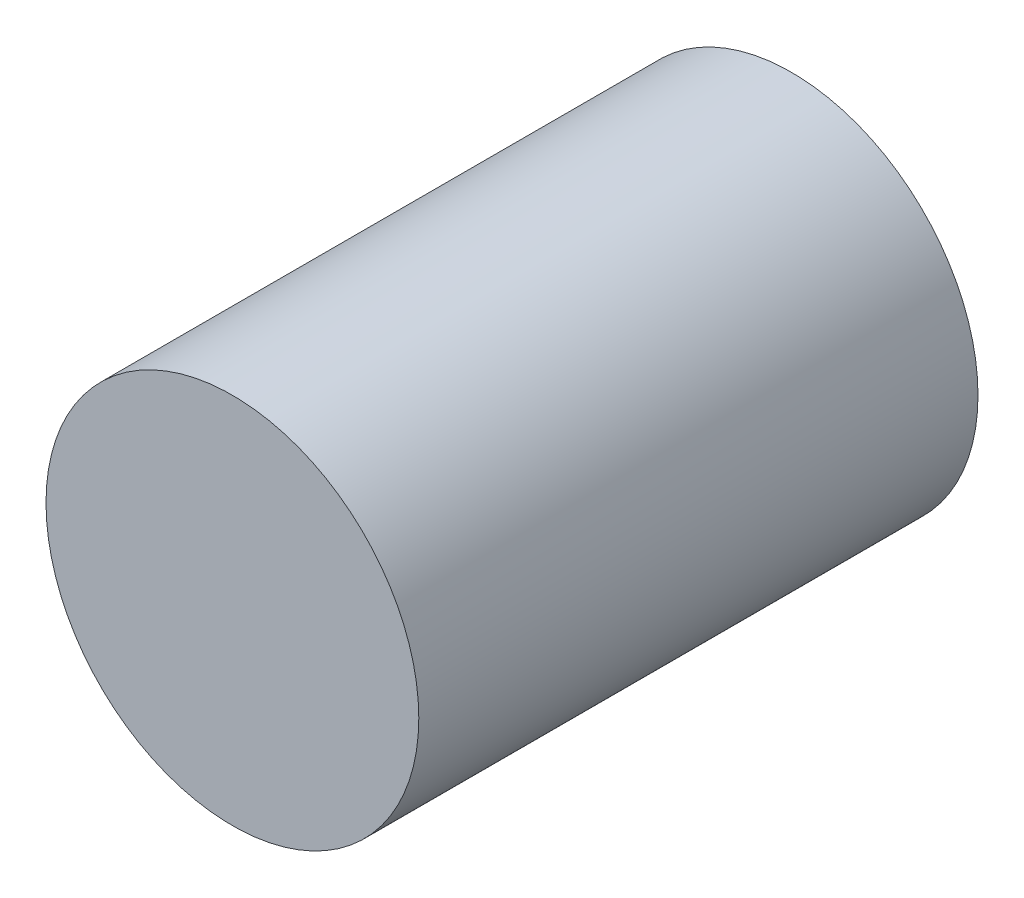
SolidWorks part; units mm, degrees
ref_plane "前视基准面" through (0, 0, 0) normal (0, 0, 1) x (1, 0, 0)
ref_plane "上视基准面" through (0, 0, 0) normal (0, 1, 0) x (1, 0, 0)
ref_plane "右视基准面" through (0, 0, 0) normal (1, 0, 0) x (0, 0, -1)
other "Configuration Table"
sketch "草图1" plane through (0, 0, 0) normal (0, 0, 1) x (1, 0, 0)
  circle A0 centre (0, 0) radius 4
  dimension "D1" = 8
extrude "凸台-拉伸1" add sketch "草图1" along normal blind 12
